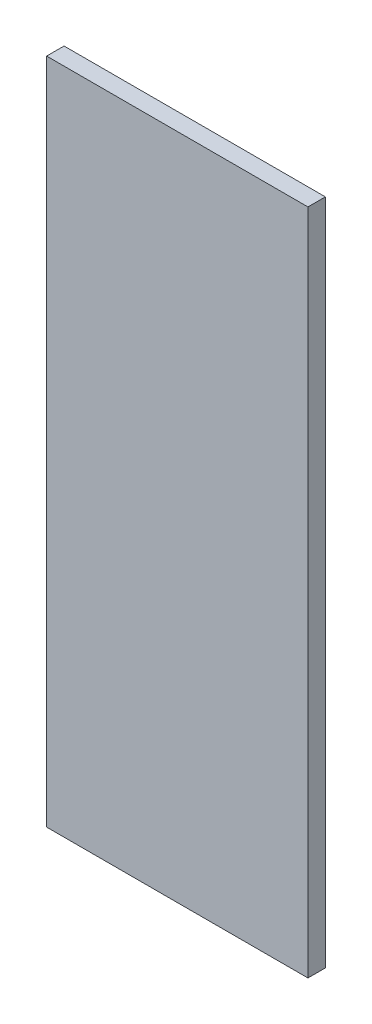
SolidWorks part; units mm, degrees
ref_plane "前视基准面" through (0, 0, 0) normal (0, 0, 1) x (1, 0, 0)
ref_plane "上视基准面" through (0, 0, 0) normal (0, 1, 0) x (1, 0, 0)
ref_plane "右视基准面" through (0, 0, 0) normal (1, 0, 0) x (0, 0, -1)
sketch "草图1" plane through (0, 0, 0) normal (0, 0, 1) x (1, 0, 0)
  line L1 (0, 0) -> (90, 0)
  line L2 (0, 0) -> (0, 230)
  line L3 (0, 230) -> (90, 230)
  line L4 (90, 0) -> (90, 230)
extrude "凸台-拉伸1" add sketch "草图1" along normal blind 6
